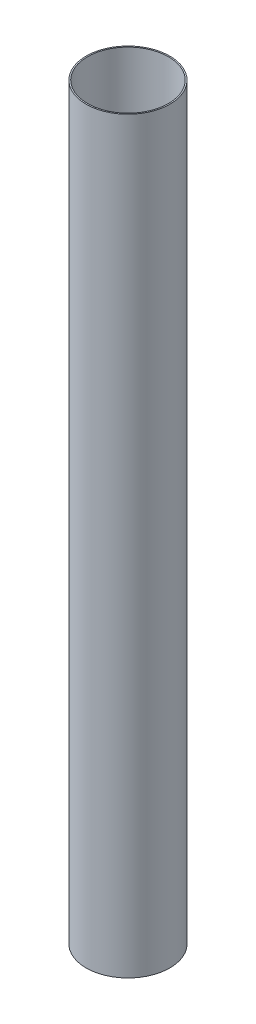
SolidWorks part; units mm, degrees
material "Balsa"
ref_plane "Front Plane" through (0, 0, 0) normal (0, 0, 1) x (1, 0, 0)
ref_plane "Top Plane" through (0, 0, 0) normal (0, 1, 0) x (1, 0, 0)
ref_plane "Right Plane" through (0, 0, 0) normal (1, 0, 0) x (0, 0, -1)
sketch "Sketch1" plane through (0, 0, 0) normal (0, 1, 0) x (1, 0, 0)
  circle A0 centre (0, 0) radius 51.105
  dimension "D1" = 102.21
extrude "Boss-Extrude1" add sketch "Sketch1" along normal blind 914.4
sketch "Sketch3" plane through (0, 0, 0) normal (0, -1, 0) x (1, 0, 0)
  circle A0 centre (0, 0) radius 49.53
  dimension "D1" = 99.06
extrude "Cut-Extrude1" cut sketch "Sketch3" against normal through all
